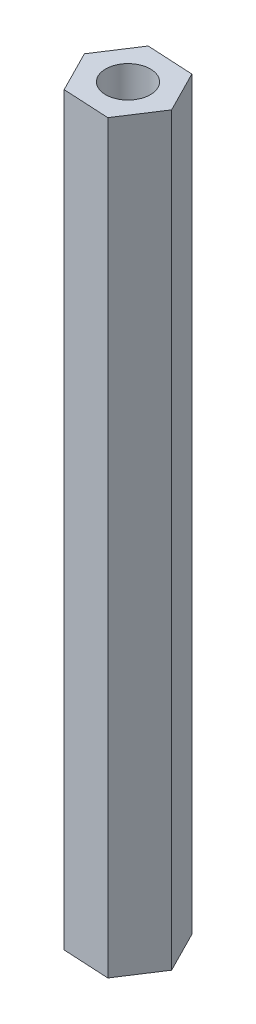
SolidWorks part; units mm, degrees
ref_plane "前视基准面" through (0, 0, 0) normal (0, 0, 1) x (1, 0, 0)
ref_plane "上视基准面" through (0, 0, 0) normal (0, 1, 0) x (1, 0, 0)
ref_plane "右视基准面" through (0, 0, 0) normal (1, 0, 0) x (0, 0, -1)
other "Configuration Table"
sketch "草图1" plane through (0, 0, 0) normal (0, 1, 0) x (1, 0, 0)
  line L1 (3.4015, -0.1819) -> (1.8583, 2.8548)
  line L2 (1.8583, 2.8548) -> (-1.5432, 3.0368)
  line L3 (-1.5432, 3.0368) -> (-3.4015, 0.1819)
  line L4 (-3.4015, 0.1819) -> (-1.8583, -2.8548)
  line L5 (-1.8583, -2.8548) -> (1.5432, -3.0368)
  line L6 (1.5432, -3.0368) -> (3.4015, -0.1819)
  circle A0 centre (0, 0) radius 2.95 construction
  dimension "D1" = 5.9
extrude "凸台-拉伸1" add sketch "草图1" along normal blind 55
hole_wizard "M4 螺纹孔1" positions "草图2" profile "草图3" tap size "M4" standard "GB" end condition through all
sketch "草图2" plane through (0, 55, 0) normal (0, 1, 0) x (1, 0, 0)
  point P0 (0, 0)
sketch "草图3" plane through (0, 55, 0) normal (1, 0, 0) x (0, 0, 1)
  line L0 (0, 0) -> (0, 55)
  line L1 (0, 55) -> (1.65, 55)
  line L2 (1.65, 55) -> (1.65, 0)
  line L5 (1.65, 0) -> (0, 0)
  line L11 (0, -6.35) -> (0, 107.95) construction
  dimension "通孔螺纹孔钻头直径" = 3.3
  dimension "通孔螺纹孔钻头深度" = 55
cosmetic thread "孔螺纹线1" parameters "D2"=4
